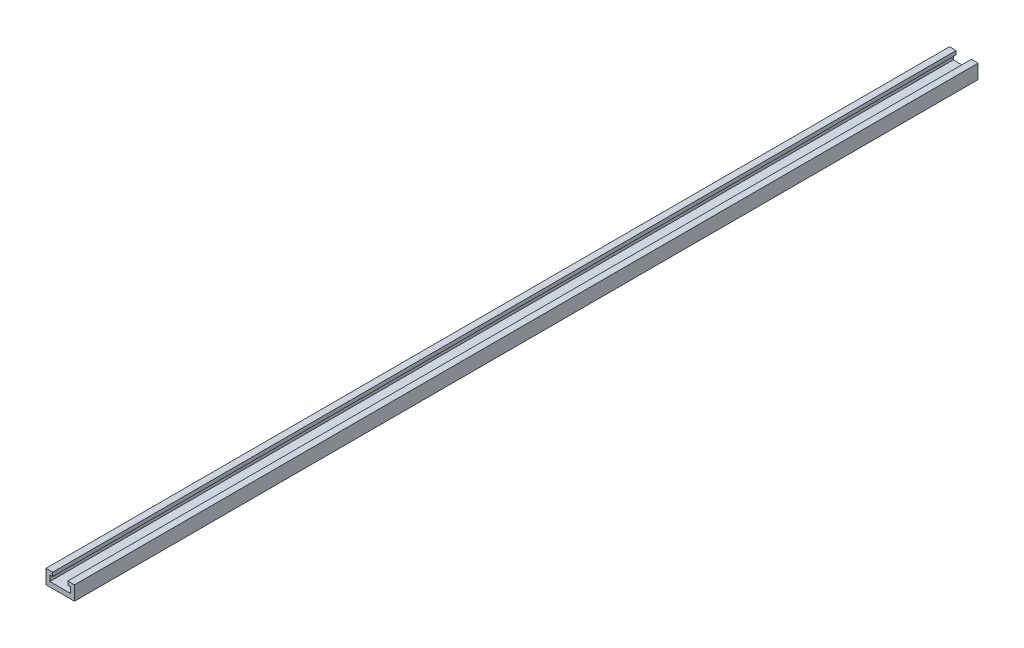
SolidWorks part; units mm, degrees
ref_plane "Front Plane" through (0, 0, 0) normal (0, 0, 1) x (1, 0, 0)
ref_plane "Top Plane" through (0, 0, 0) normal (0, 1, 0) x (1, 0, 0)
ref_plane "Right Plane" through (0, 0, 0) normal (1, 0, 0) x (0, 0, -1)
sketch "Sketch2" plane through (0, 0, 0) normal (0, 0, 1) x (1, 0, 0)
  line L0 (4.445, 9.525) -> (4.445, 6.985)
  line L1 (0, 0) -> (19.05, 0)
  line L2 (0, 0) -> (0, 9.525)
  line L3 (0, 9.525) -> (4.445, 9.525)
  line L4 (19.05, 0) -> (19.05, 9.525)
  line L5 (4.445, 6.985) -> (2.54, 6.985)
  line L6 (2.54, 6.985) -> (2.54, 3.175)
  line L7 (9.525, 0) -> (9.525, 3.175) construction
  line L8 (2.54, 3.175) -> (16.51, 3.175)
  line L9 (16.51, 6.985) -> (16.51, 3.175)
  line L10 (14.605, 6.985) -> (16.51, 6.985)
  line L11 (14.605, 9.525) -> (14.605, 6.985)
  line L12 (14.605, 9.525) -> (19.05, 9.525)
  point P13 (9.525, 3.175)
  dimension "D1" = 9.525
  dimension "D2" = 19.05
  dimension "D3" = 10.16
  dimension "D4" = 13.97
  dimension "D5" = 3.81
  dimension "D6" = 3.175
extrude "Boss-Extrude1" add sketch "Sketch2" along normal mid plane 603.25
